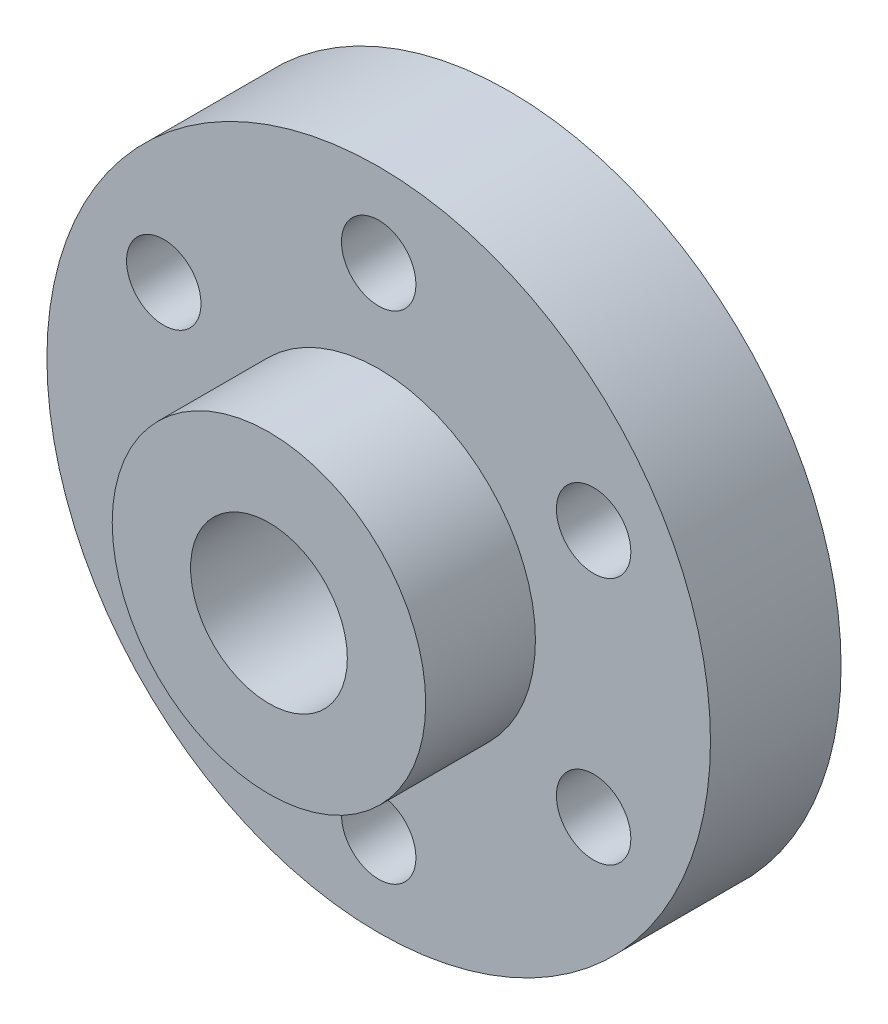
SolidWorks part; units mm, degrees
ref_plane "Front Plane" through (0, 0, 0) normal (0, 0, 1) x (1, 0, 0)
ref_plane "Top Plane" through (0, 0, 0) normal (0, 1, 0) x (1, 0, 0)
ref_plane "Right Plane" through (0, 0, 0) normal (1, 0, 0) x (0, 0, -1)
sketch "Sketch1" plane through (0, 0, 0) normal (0, 0, 1) x (1, 0, 0)
  circle A0 centre (0, 0) radius 12.7
  dimension "D1" = 25.4
extrude "Boss-Extrude1" add sketch "Sketch1" along normal blind 5
sketch "Sketch2" plane through (0, 0, 5) normal (0, 0, 1) x (1, 0, 0)
  circle A0 centre (0, 0) radius 6
extrude "Boss-Extrude2" add sketch "Sketch2" along normal blind 4.2
sketch "Sketch3" plane through (0, 0, 5) normal (0, 0, 1) x (1, 0, 0)
  arc A0 (-8.8452, 3.466) -> (-8.8452, -3.466) centre (0, 0) ccw
  circle A1 centre (0, 9.5) radius 1.425
  circle A2 centre (8.2272, 4.75) radius 1.425
  circle A3 centre (8.2272, -4.75) radius 1.425
  circle A4 centre (0, -9.5) radius 1.425
  circle A5 centre (-8.2272, -4.75) radius 1.425
  circle A6 centre (-8.2272, 4.75) radius 1.425
  arc A7 (-7.4242, -5.9272) -> (-1.421, -9.3931) centre (0, 0) ccw
  arc A8 (1.421, -9.3931) -> (7.4242, -5.9272) centre (0, 0) ccw
  arc A9 (8.8452, -3.466) -> (8.8452, 3.466) centre (0, 0) ccw
  arc A10 (7.4242, 5.9272) -> (1.421, 9.3931) centre (0, 0) ccw
  arc A11 (-1.421, 9.3931) -> (-7.4242, 5.9272) centre (0, 0) ccw
  point P18 (0, 0)
  dimension "D1" = 19
  dimension "D2" = 2.85
  dimension "D3" = 6
extrude "Cut-Extrude1" cut sketch "Sketch3" against normal up to next contours A1 | A6 | A5 | A4 | A3 | A2
sketch "Sketch4" plane through (0, 0, 9.2) normal (0, 0, 1) x (1, 0, 0)
  circle A0 centre (0, 0) radius 3
extrude "Cut-Extrude2" cut sketch "Sketch4" against normal through all both and the other way through all
